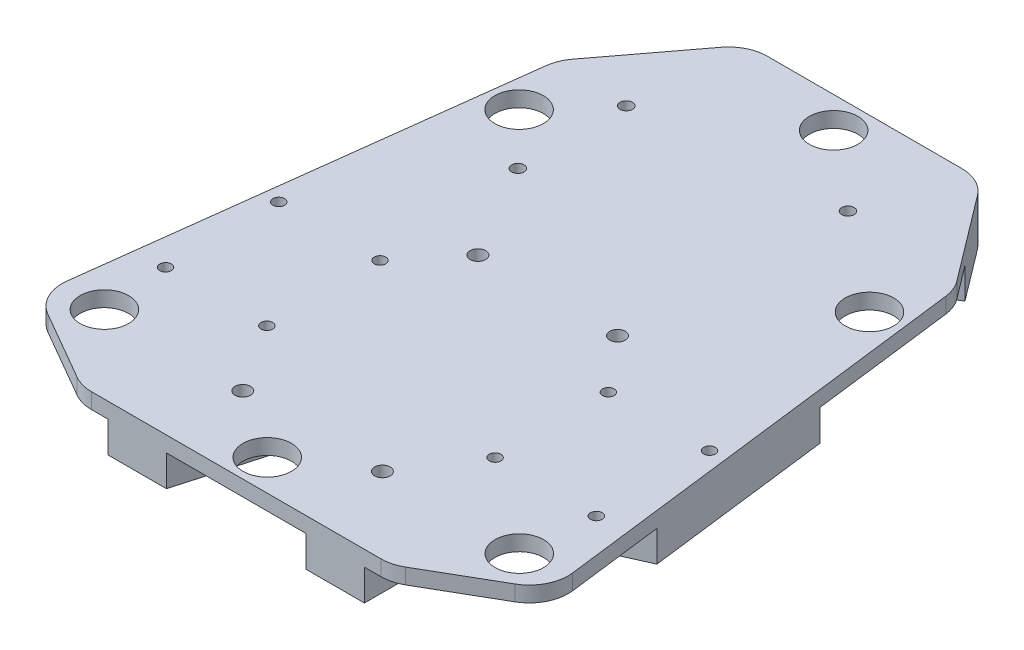
SolidWorks part; units mm, degrees
ref_plane "Front Plane" through (0, 0, 0) normal (0, 0, 1) x (1, 0, 0)
ref_plane "Top Plane" through (0, 0, 0) normal (0, 1, 0) x (1, 0, 0)
ref_plane "Right Plane" through (0, 0, 0) normal (1, 0, 0) x (0, 0, -1)
sketch "Sketch1" plane through (0, 0, 0) normal (0, 1, 0) x (1, 0, 0)
  line L0 (2.6795, 0) -> (77.3205, 0)
  line L1 (82.3205, 1.3397) -> (100.2386, 11.6848)
  line L7 (-20.2386, 11.6848) -> (-2.3205, 1.3397)
  line L8 (-25.1621, 21.5797) -> (-11.4951, 131.4228)
  line L9 (-9.5482, 136.2191) -> (6.9435, 158.031)
  line L10 (14.9201, 162) -> (65.0799, 162)
  line L11 (73.0565, 158.031) -> (89.5482, 136.2191)
  line L12 (91.4951, 131.4228) -> (105.1621, 21.5797)
  line L13 (-11.1643, 134.0818) -> (91.1643, 134.0818) construction
  line L14 (40, 162) -> (40, 154) construction
  line L15 (40, 8) -> (40, 0) construction
  circle A2 centre (-13.9808, 20) radius 6.25
  circle A6 centre (93.9808, 19) radius 6.25
  circle A7 centre (-5.1643, 118.0818) radius 6.25
  circle A8 centre (85.1643, 118.0818) radius 6.25
  circle A9 centre (40, 154) radius 6.25
  circle A10 centre (40, 8) radius 6.25
  arc A13 (-11.4951, 131.4228) -> (-9.5482, 136.2191) centre (-1.5716, 130.1881) cw
  arc A14 (-25.1621, 21.5797) -> (-20.2386, 11.6848) centre (-15.2386, 20.345) ccw
  arc A15 (2.6795, 0) -> (-2.3205, 1.3397) centre (2.6795, 10) cw
  arc A16 (77.3205, 0) -> (82.3205, 1.3397) centre (77.3205, 10) ccw
  arc A17 (100.2386, 11.6848) -> (105.1621, 21.5797) centre (95.2386, 20.345) ccw
  arc A18 (89.5482, 136.2191) -> (91.4951, 131.4228) centre (81.5716, 130.1881) cw
  arc A19 (65.0799, 162) -> (73.0565, 158.031) centre (65.0799, 152) cw
  arc A20 (6.9435, 158.031) -> (14.9201, 162) centre (14.9201, 152) cw
  point P14 (-11.2796, 6.5123)
  point P17 (40, 162)
  point P29 (-25.9808, 15)
  point P32 (0, 0)
  point P35 (80, 0)
  point P39 (105.9808, 15)
  point P47 (9.9443, 162)
  dimension "D10" = 12.5
  dimension "D9" = 150
  dimension "D11" = 16
  dimension "D20" = 10
  dimension "D1" = 80
  dimension "D2" = 150
  dimension "D3" = 150
  dimension "D4" = 30
  dimension "D5" = 162
  dimension "D6" = 120
  dimension "D7" = 35
  dimension "D8" = 150
  dimension "D12" = 6
  dimension "D13" = 16
  dimension "D14" = 6
  dimension "D15" = 8
  dimension "D16" = 8
  dimension "D17" = 12
  dimension "D18" = 4
  dimension "4" = 5
  dimension "D19" = 12
extrude "Boss-Extrude2" add sketch "Sketch1" along normal blind 12
sketch "Sketch2" plane through (0, 12, 0) normal (0, 1, 0) x (1, 0, 0)
  line L0 (2.6795, 0) -> (77.3205, 0) construction
  line L1 (5.8395, 140.3635) -> (73.8395, 140.3635)
  line L2 (5.8395, 140.3635) -> (5.8395, 89.8635)
  line L3 (5.8395, 89.8635) -> (73.8395, 89.8635)
  line L4 (73.8395, 140.3635) -> (73.8395, 89.8635)
  line L23 (95.3083, 120.3398) -> (88.2807, 127.9958)
  line L24 (88.2807, 127.9958) -> (78.1367, 125.7377)
  line L25 (78.1367, 125.7377) -> (75.0202, 115.8237)
  line L26 (75.0202, 115.8237) -> (82.0478, 108.1678)
  line L27 (82.0478, 108.1678) -> (92.1918, 110.4258)
  line L28 (92.1918, 110.4258) -> (95.3083, 120.3398)
  line L29 (-14.8332, 121.8911) -> (-13.2977, 111.6129)
  line L30 (-13.2977, 111.6129) -> (-3.6287, 107.8035)
  line L31 (-3.6287, 107.8035) -> (4.5047, 114.2725)
  line L32 (4.5047, 114.2725) -> (2.9692, 124.5507)
  line L33 (2.9692, 124.5507) -> (-6.6998, 128.36)
  line L34 (-6.6998, 128.36) -> (-14.8332, 121.8911)
  line L35 (50.3127, 155.2841) -> (44.0443, 163.5731)
  line L36 (44.0443, 163.5731) -> (33.7316, 162.289)
  line L37 (33.7316, 162.289) -> (29.6873, 152.7159)
  line L38 (29.6873, 152.7159) -> (35.9557, 144.4269)
  line L39 (35.9557, 144.4269) -> (46.2684, 145.711)
  line L40 (46.2684, 145.711) -> (50.3127, 155.2841)
  line L41 (50.3923, 8) -> (45.1962, 17)
  line L42 (45.1962, 17) -> (34.8038, 17)
  line L43 (34.8038, 17) -> (29.6077, 8)
  line L44 (29.6077, 8) -> (34.8038, -1)
  line L45 (34.8038, -1) -> (45.1962, -1)
  line L46 (45.1962, -1) -> (50.3923, 8)
  line L47 (104.2997, 20.2328) -> (98.0725, 28.5529)
  line L48 (98.0725, 28.5529) -> (87.7536, 27.32)
  line L49 (87.7536, 27.32) -> (83.6618, 17.7672)
  line L50 (83.6618, 17.7672) -> (89.889, 9.4471)
  line L51 (89.889, 9.4471) -> (100.2079, 10.68)
  line L52 (100.2079, 10.68) -> (104.2997, 20.2328)
  line L53 (-24.3731, 20) -> (-19.1769, 11)
  line L54 (-19.1769, 11) -> (-8.7846, 11)
  line L55 (-8.7846, 11) -> (-3.5885, 20)
  line L56 (-3.5885, 20) -> (-8.7846, 29)
  line L57 (-8.7846, 29) -> (-19.1769, 29)
  line L58 (-19.1769, 29) -> (-24.3731, 20)
  line L59 (40, 162) -> (40, 0) construction
  line L60 (65.0799, 162) -> (14.9201, 162) construction
  line L62 (22, 78) -> (58, 78)
  line L63 (22, 78) -> (22, 32)
  line L64 (22, 32) -> (58, 32)
  line L65 (58, 78) -> (58, 32)
  circle A0 centre (40, 55) radius 13
  circle A1 centre (85.1643, 118.0818) radius 9 construction
  circle A2 centre (-5.1643, 118.0818) radius 9 construction
  circle A3 centre (40, 154) radius 9 construction
  circle A4 centre (40, 8) radius 9 construction
  circle A5 centre (93.9808, 19) radius 9 construction
  circle A6 centre (-13.9808, 20) radius 9 construction
  dimension "D9" = 26
  dimension "D10" = 18
  dimension "D1" = 68
  dimension "D2" = 50.5
  dimension "D3" = 36
  dimension "D4" = 46
  dimension "D5" = 23
  dimension "D6" = 18
  dimension "D11" = 55
sketch "Sketch3" plane through (0, 12, 0) normal (0, 1, 0) x (1, 0, 0)
  line L0 (73.8395, 140.3635) -> (7.7995, 140.3635) construction
  line L1 (5.8395, 140.3635) -> (73.8395, 140.3635) construction
  line L2 (7.7995, 140.3635) -> (7.7995, 104.8035) construction
  line L3 (65.0799, 162) -> (14.9201, 162) construction
  line L4 (59.8695, 140.3635) -> (59.8695, 137.8235) construction
  line L5 (40, 162) -> (73.8395, 162) construction
  line L6 (73.8395, 162) -> (73.8395, 140.3635) construction
  line L7 (40, 0) -> (40, 162) construction
  line L8 (58, 50) -> (22, 50) construction
  line L10 (58, 78) -> (58, 32) construction
  line L11 (58, 50) -> (58, 19.7) construction
  line L13 (-17.9728, 69.4043) -> (10.5772, 69.4043) construction
  line L14 (-17.9728, 69.4043) -> (-17.9728, 37.3143) construction
  line L15 (-15.5228, 69.4043) -> (-15.5228, 66.4943) construction
  line L16 (-15.5228, 66.4943) -> (-17.9728, 66.4943) construction
  line L17 (-17.9728, 37.3143) -> (-15.5228, 37.3143) construction
  line L18 (10.5772, 69.4043) -> (10.5772, 37.3143) construction
  line L19 (10.5772, 37.3143) -> (-15.5228, 37.3143) construction
  line L20 (-15.5228, 66.4943) -> (10.5772, 66.4943) construction
  line L21 (-15.5228, 37.3143) -> (-15.5228, 66.4943) construction
  line L22 (95.5228, 37.3143) -> (95.5228, 66.4943) construction
  line L23 (69.4228, 37.3143) -> (95.5228, 37.3143) construction
  line L24 (97.9728, 37.3143) -> (95.5228, 37.3143) construction
  line L25 (95.5228, 66.4943) -> (97.9728, 66.4943) construction
  line L26 (95.5228, 69.4043) -> (95.5228, 66.4943) construction
  line L27 (97.9728, 69.4043) -> (97.9728, 37.3143) construction
  line L28 (95.5228, 66.4943) -> (69.4228, 66.4943) construction
  line L29 (69.4228, 69.4043) -> (69.4228, 37.3143) construction
  line L30 (97.9728, 69.4043) -> (69.4228, 69.4043) construction
  line L31 (22, 80.3) -> (22, 50) construction
  line L32 (58, 50) -> (58, 80.3) construction
  line L33 (22, 50) -> (22, 19.7) construction
  circle A0 centre (7.7995, 104.8035) radius 1.6
  circle A1 centre (7.7995, 132.7435) radius 1.6
  circle A2 centre (59.8695, 137.8235) radius 1.6
  circle A3 centre (58, 19.7) radius 2
  circle A4 centre (22, 19.7) radius 2
  circle A5 centre (22, 80.3) radius 2
  circle A6 centre (58, 80.3) radius 2
  circle A7 centre (10.5772, 37.3143) radius 1.5
  circle A8 centre (-15.5228, 66.4943) radius 1.5
  circle A9 centre (-15.5228, 37.3143) radius 1.5
  circle A10 centre (10.5772, 66.4943) radius 1.5
  circle A11 centre (95.5228, 37.3143) radius 1.5
  circle A12 centre (95.5228, 66.4943) radius 1.5
  circle A13 centre (69.4228, 37.3143) radius 1.5
  circle A14 centre (69.4228, 66.4943) radius 1.5
  point P0 (73.8395, 140.3635)
  point P13 (40, 162)
  point P36 (-17.9728, 69.4043)
  point P62 (97.9728, 69.4043)
  dimension "D3" = 7.62
  dimension "D6" = 3.2
  dimension "D9" = 4
  dimension "D10" = 28.55
  dimension "D1" = 66.04
  dimension "D2" = 35.56
  dimension "D4" = 13.97
  dimension "D5" = 2.54
  dimension "D7" = 36
  dimension "D8" = 30.3
  dimension "D11" = 32.09
  dimension "D12" = 2.91
  dimension "D13" = 2.45
extrude "Cut-Extrude3" cut sketch "Sketch3" against normal through all
sketch "Sketch4" plane through (0, 0, 0) normal (0, -1, 0) x (1, 0, 0)
  line L0 (82.3205, -1.3397) -> (100.2386, -11.6848) construction
  line L1 (91.4951, -131.4228) -> (105.1621, -21.5797) construction
  line L2 (73.0565, -158.031) -> (89.5482, -136.2191) construction
  line L3 (14.9201, -162) -> (65.0799, -162) construction
  line L4 (-9.5482, -136.2191) -> (6.9435, -158.031) construction
  line L5 (-25.1621, -21.5797) -> (-11.4951, -131.4228) construction
  line L6 (-20.2386, -11.6848) -> (-2.3205, -1.3397) construction
  line L7 (2.6795, 0) -> (77.3205, 0) construction
  line L8 (82.3205, -1.3397) -> (100.2386, -11.6848)
  line L9 (91.4951, -131.4228) -> (96.111, -94.324)
  line L10 (73.0565, -158.031) -> (89.5482, -136.2191)
  line L11 (22.0218, -162) -> (57.9782, -162)
  line L12 (-9.5482, -136.2191) -> (-3.0702, -144.787)
  line L13 (-25.1621, -21.5797) -> (-22.0775, -46.3712)
  line L14 (-20.2386, -11.6848) -> (-2.3205, -1.3397)
  line L15 (2.6795, 0) -> (6.9435, 0)
  line L16 (-22.0775, -46.3712) -> (6.9435, -33.4412)
  line L17 (6.9435, -33.4412) -> (6.9435, 0)
  line L18 (40, 0) -> (40, -162) construction
  line L19 (22.0218, 0) -> (28.8072, -24.0025)
  line L20 (28.8072, -24.0025) -> (51.1928, -24.0025)
  line L21 (-16.111, -94.324) -> (14.9201, -99.7631)
  line L22 (14.9201, -99.7631) -> (14.9201, -134.0818)
  line L23 (-11.1643, -134.0818) -> (91.1643, -134.0818) construction
  line L24 (14.9201, -134.0818) -> (-3.0702, -144.787)
  line L25 (22.0218, -162) -> (27.4116, -138.3331)
  line L26 (27.4116, -138.3331) -> (52.5884, -138.3331)
  line L27 (57.9782, -162) -> (52.5884, -138.3331)
  line L28 (65.0799, -134.0818) -> (83.0702, -144.787)
  line L29 (96.111, -94.324) -> (65.0799, -99.7631)
  line L30 (65.0799, -99.7631) -> (65.0799, -134.0818)
  line L31 (57.9782, 0) -> (51.1928, -24.0025)
  line L32 (102.0775, -46.3712) -> (73.0565, -33.4412)
  line L33 (73.0565, -33.4412) -> (73.0565, 0)
  line L34 (-16.111, -94.324) -> (-11.4951, -131.4228)
  line L35 (102.0775, -46.3712) -> (105.1621, -21.5797)
  line L36 (22.0218, 0) -> (77.3205, 0)
  line L37 (22.0218, 0) -> (57.9782, 0)
  line L38 (73.0565, 0) -> (77.3205, 0)
  line L39 (83.0702, -144.787) -> (89.5482, -136.2191)
  arc A0 (2.6795, 0) -> (-2.3205, -1.3397) centre (2.6795, -10) ccw construction
  arc A1 (105.1621, -21.5797) -> (100.2386, -11.6848) centre (95.2386, -20.345) ccw construction
  arc A2 (82.3205, -1.3397) -> (77.3205, 0) centre (77.3205, -10) ccw construction
  arc A3 (89.5482, -136.2191) -> (91.4951, -131.4228) centre (81.5716, -130.1881) ccw construction
  arc A4 (-11.4951, -131.4228) -> (-9.5482, -136.2191) centre (-1.5716, -130.1881) ccw construction
  arc A5 (6.9435, -158.031) -> (14.9201, -162) centre (14.9201, -152) ccw construction
  arc A7 (-20.2386, -11.6848) -> (-25.1621, -21.5797) centre (-15.2386, -20.345) ccw construction
  arc A8 (2.6795, 0) -> (-2.3205, -1.3397) centre (2.6795, -10) ccw
  arc A9 (105.1621, -21.5797) -> (100.2386, -11.6848) centre (95.2386, -20.345) ccw
  arc A10 (82.3205, -1.3397) -> (77.3205, 0) centre (77.3205, -10) ccw
  arc A11 (89.5482, -136.2191) -> (91.4951, -131.4228) centre (81.5716, -130.1881) ccw
  arc A12 (-11.4951, -131.4228) -> (-9.5482, -136.2191) centre (-1.5716, -130.1881) ccw
  arc A15 (-20.2386, -11.6848) -> (-25.1621, -21.5797) centre (-15.2386, -20.345) ccw
  point P0 (80, 0)
  point P45 (40, -138.3331)
  point P51 (40, -24.0025)
  circle M33 centre (-15.5228, -37.3143) radius 1.5
  circle M40 centre (7.7995, -132.7435) radius 1.6
  circle M44 centre (95.5228, -37.3143) radius 1.5
  circle M47 centre (7.7995, -104.8035) radius 1.6
  circle M48 centre (85.1643, -118.0818) radius 6.25
  circle M49 centre (93.9808, -19) radius 6.25
  circle M50 centre (-13.9808, -20) radius 6.25
  arc M51 (-11.4951, -131.4228) -> (-9.5482, -136.2191) centre (-1.5716, -130.1881) ccw
  line M52 (-9.5482, -136.2191) -> (6.9435, -158.031)
  line M54 (14.9201, -162) -> (65.0799, -162)
  arc M57 (89.5482, -136.2191) -> (91.4951, -131.4228) centre (81.5716, -130.1881) ccw
  line M58 (91.4951, -131.4228) -> (105.1621, -21.5797)
  arc M59 (105.1621, -21.5797) -> (100.2386, -11.6848) centre (95.2386, -20.345) ccw
  line M60 (100.2386, -11.6848) -> (82.3205, -1.3397)
  arc M61 (82.3205, -1.3397) -> (77.3205, 0) centre (77.3205, -10) ccw
  line M62 (77.3205, 0) -> (2.6795, 0)
  arc M63 (2.6795, 0) -> (-2.3205, -1.3397) centre (2.6795, -10) ccw
  line M64 (-2.3205, -1.3397) -> (-20.2386, -11.6848)
  arc M65 (-20.2386, -11.6848) -> (-25.1621, -21.5797) centre (-15.2386, -20.345) ccw
  line M66 (-25.1621, -21.5797) -> (-11.4951, -131.4228)
  circle M67 centre (40, -8) radius 6.25
  circle M68 centre (-5.1643, -118.0818) radius 6.25
  circle M69 centre (40, -154) radius 6.25
extrude "Cut-Extrude4" cut sketch "Sketch4" against normal blind 8 contours L24 L22 L21 M66 M51 M52 M40 M68 M47 | L26 L18 L11 L27 M69 | L18 L26 L25 M54 M69 | L29 L30 L28 L10 M57 M58 M48 | L33 L32 M58 M59 M60 M61 M62 M44 M49 | L18 L20 L31 M62 M67 | L18 L37 L19 L20 M67 | L16 L17 M62 M63 M64 M65 M66 M33 M50
